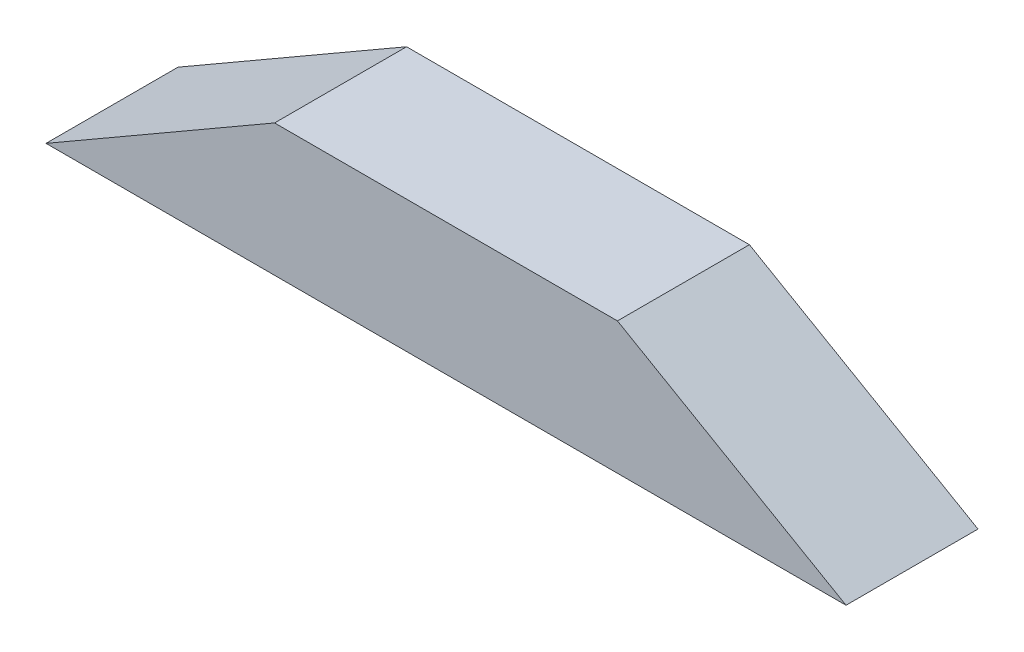
SolidWorks part; units mm, degrees
ref_plane "Front Plane" through (0, 0, 0) normal (0, 0, 1) x (1, 0, 0)
ref_plane "Top Plane" through (0, 0, 0) normal (0, 1, 0) x (1, 0, 0)
ref_plane "Right Plane" through (0, 0, 0) normal (1, 0, 0) x (0, 0, -1)
sketch "Sketch1" plane through (0, 0, 0) normal (0, 0, 1) x (1, 0, 0)
  line L0 (238.2311, -105.5794) -> (268.542, -123.0794)
  line L2 (268.542, -123.0794) -> (207.9202, -123.0794)
  line L4 (207.9202, -123.0794) -> (238.2311, -105.5794)
  line L5 (268.542, -123.0794) -> (268.542, -113.0794)
  line L6 (251.2215, -113.0794) -> (225.2408, -113.0794)
extrude "Boss-Extrude1" add sketch "Sketch1" along normal blind 10 contours L0 L6 L4 L2
